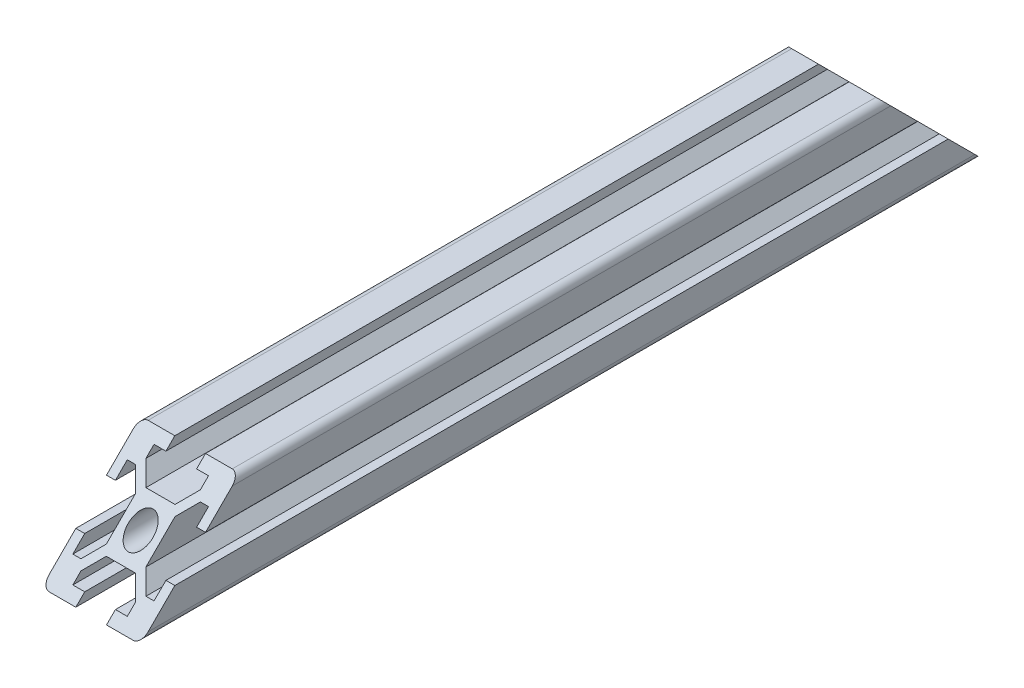
SolidWorks part; units mm, degrees
ref_plane "前视基准面" through (0, 0, 0) normal (0, 0, 1) x (1, 0, 0)
ref_plane "上视基准面" through (0, 0, 0) normal (0, 1, 0) x (1, 0, 0)
ref_plane "右视基准面" through (0, 0, 0) normal (1, 0, 0) x (0, 0, -1)
sketch "草图1" plane through (0, 0, 0) normal (0, 0, 1) x (1, 0, 0)
  line L0 (5.5, -8.2) -> (5.5, -6.5607)
  line L1 (-8.5, -10) -> (-3.1, -10)
  line L2 (-10, -8.5) -> (-10, -3.1)
  line L3 (-8.5, 10) -> (-3.1, 10)
  line L4 (10, -8.5) -> (10, -3.1)
  line L5 (-10, -10) -> (10, 10) construction
  line L6 (-10, 10) -> (10, -10) construction
  line L7 (8.2, 5.5) -> (6.5607, 5.5)
  line L8 (-2.9393, 4) -> (2.9393, 4)
  line L9 (4, 2.9393) -> (4, -2.9393)
  line L10 (2.9393, -4) -> (-2.9393, -4)
  line L11 (-4, -2.9393) -> (-4, 2.9393)
  line L12 (5.5, 6.5607) -> (5.5, 8.2)
  line L13 (6.5607, -5.5) -> (8.2, -5.5)
  line L14 (-8.2, -5.5) -> (-6.5607, -5.5)
  line L15 (-5.5, -6.5607) -> (-5.5, -8.2)
  line L16 (-5.5, 8.2) -> (-5.5, 6.5607)
  line L17 (-6.5607, 5.5) -> (-8.2, 5.5)
  line L18 (4, 2.9393) -> (6.5607, 5.5)
  line L19 (2.9393, 4) -> (5.5, 6.5607)
  line L20 (2.9393, -4) -> (5.5, -6.5607)
  line L21 (-4, 2.9393) -> (-6.5607, 5.5)
  line L22 (4, -2.9393) -> (6.5607, -5.5)
  line L23 (-2.9393, 4) -> (-5.5, 6.5607)
  line L24 (-4, -2.9393) -> (-6.5607, -5.5)
  line L25 (-2.9393, -4) -> (-5.5, -6.5607)
  line L26 (8.2, 3.1) -> (8.2, 5.5)
  line L27 (8.2, 3.1) -> (10, 3.1)
  line L28 (3.1, -8.2) -> (5.5, -8.2)
  line L29 (3.1, -8.2) -> (3.1, -10)
  line L30 (8.2, -3.1) -> (10, -3.1)
  line L31 (8.2, -3.1) -> (8.2, -5.5)
  line L32 (-3.1, -8.2) -> (-3.1, -10)
  line L33 (-3.1, -8.2) -> (-5.5, -8.2)
  line L34 (-8.2, -3.1) -> (-8.2, -5.5)
  line L35 (-8.2, -3.1) -> (-10, -3.1)
  line L36 (-8.2, 3.1) -> (-10, 3.1)
  line L37 (-8.2, 3.1) -> (-8.2, 5.5)
  line L38 (-3.1, 8.2) -> (-5.5, 8.2)
  line L39 (-3.1, 8.2) -> (-3.1, 10)
  line L40 (3.1, 8.2) -> (3.1, 10)
  line L41 (3.1, 8.2) -> (5.5, 8.2)
  line L42 (10, 3.1) -> (10, 8.5)
  line L43 (3.1, 10) -> (8.5, 10)
  line L44 (-10, 3.1) -> (-10, 8.5)
  line L45 (3.1, -10) -> (8.5, -10)
  arc A0 (8.5, -10) -> (10, -8.5) centre (8.5, -8.5) ccw
  arc A1 (-10, 8.5) -> (-8.5, 10) centre (-8.5, 8.5) cw
  arc A2 (-8.5, -10) -> (-10, -8.5) centre (-8.5, -8.5) cw
  arc A3 (8.5, 10) -> (10, 8.5) centre (8.5, 8.5) cw
  circle A4 centre (0, 0) radius 2.5
  point P0 (0, 0)
  point P39 (0, 0)
  point P56 (0, 0)
  point P73 (0, 0)
  dimension "D3" = 1.5
  dimension "D4" = 4
  dimension "D1" = 20
  dimension "D5" = 4
  dimension "D6" = 4
extrude "凸台-拉伸2" add sketch "草图1" against normal blind 170
scale "Scale1" bodies to scale 107 scale about origin uniform scaling yes scale factor 2.5
ref_plane "Plane1" through (0, 200, -200) normal (0, 0.7071, -0.7071) x (1, 0, 0)
sketch "Sketch1" plane through (0, 200, -200) normal (0, 0.7071, -0.7071) x (1, 0, 0)
  line L1 (-31.8197, 319.2638) -> (34.4299, 319.2638)
  line L2 (-31.8197, 319.2638) -> (-31.8197, 233.3066)
  line L3 (-31.8197, 233.3066) -> (34.4299, 233.3066)
  line L4 (34.4299, 319.2638) -> (34.4299, 233.3066)
  point P4 (0, 0)
  point P5 (0, 0)
extrude "Cut-Extrude1" cut sketch "Sketch1" along normal blind 50
ref_plane "Plane3" through (0, 0, -425) normal (0, 0, 1) x (1, 0, 0)
ref_plane "Plane4" through (0, 0, -212.5) normal (0, 0, 1) x (1, 0, 0)
mirror "Mirror1" about plane through (0, 0, -212.5) normal (0, 0, 1) of "Cut-Extrude1"
